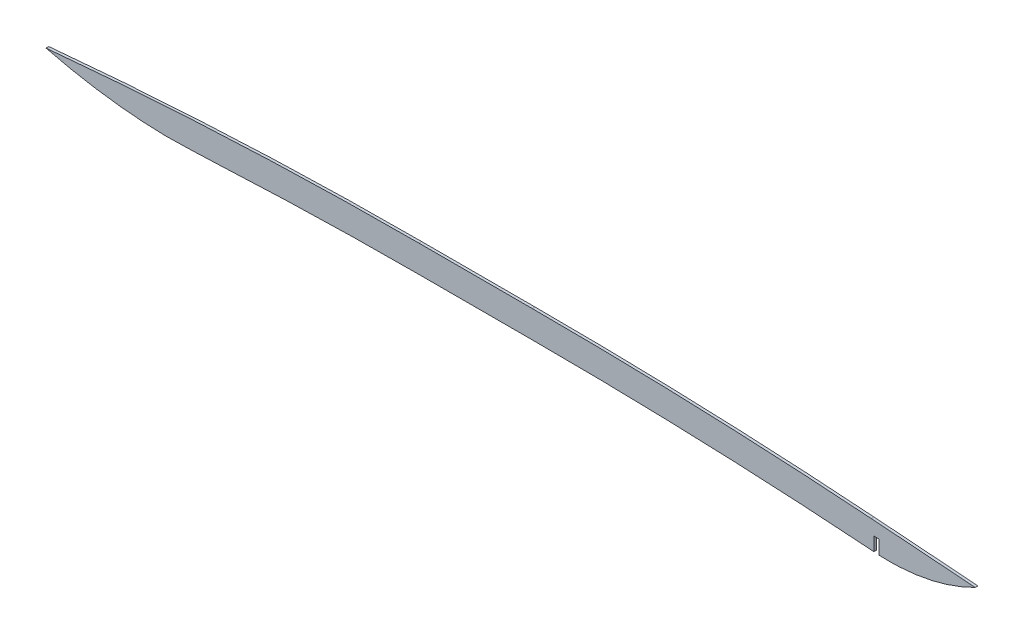
SolidWorks part; units mm, degrees
ref_plane "Front Plane" through (0, 0, 0) normal (0, 0, 1) x (1, 0, 0)
ref_plane "Top Plane" through (0, 0, 0) normal (0, 1, 0) x (1, 0, 0)
ref_plane "Right Plane" through (0, 0, 0) normal (1, 0, 0) x (0, 0, -1)
sketch "Sketch1" plane through (0, 0, 0) normal (0, 0, 1) x (1, 0, 0)
  line L2 (1659.5661, -5.4123) -> (2076.8952, -5.4123)
  line L3 (1659.5661, 94.5877) -> (2076.8952, 94.5877)
  arc A11 (3324.9617, 49.0573) -> (2946.0697, 72.5208) centre (2076.8952, -17033.9956) ccw
  arc A12 (2946.0697, 72.5208) -> (2677.8035, 84.0439) centre (2076.8952, -17033.9956) ccw
  arc A14 (1659.5661, -5.4123) -> (927.3706, -23.9029) centre (1659.5661, -14511.4611) ccw
  arc A15 (2674.2953, -15.8945) -> (2076.8952, -5.4123) centre (2076.8952, -17033.9956) ccw
  arc A16 (2940.9953, -27.3504) -> (2674.2953, -15.8945) centre (2076.8952, -17033.9956) ccw
  arc A17 (3317.6753, -50.6769) -> (2940.9953, -27.3504) centre (2076.8952, -17033.9956) ccw
  arc A18 (3701.2123, -79.0448) -> (3317.6753, -50.6769) centre (-16248.6371, -267195.9745) ccw
  arc A19 (4283.8008, -123.092) -> (3701.2123, -79.0448) centre (-16201.7377, -267199.4731) ccw
  arc A20 (2677.8035, 84.0439) -> (2076.8952, 94.5877) centre (2076.8952, -17033.9956) ccw
  arc A21 (1659.5661, 94.5877) -> (689.0096, 62.3058) centre (1659.5661, -14511.4611) ccw
  arc A22 (689.0096, 62.3058) -> (286.2522, 29.8824) centre (1659.5661, -14511.4611) ccw
  arc A23 (286.2522, 29.8824) -> (0, 0) centre (1659.5661, -14511.4611) ccw
  arc A24 (4636.8918, -50.106) -> (3708.6426, 20.6788) centre (-16201.7377, -267199.4731) ccw
  arc A25 (3708.6426, 20.6788) -> (3324.9617, 49.0573) centre (-16248.637, -267195.9745) ccw
  spline S0 degree 2 poles (0, 0) (462.6118, -45.5045) (927.3706, -23.9029) knots 0 0 0 1 1 1
  spline S1 degree 2 poles (4636.8918, -50.106) (4468.4256, -123.0197) (4283.8008, -123.092) knots 0 0 0 1 1 1
  spline S2 degree 2 poles (3708.6426, 20.6788) (3526.2676, -70.9076) (3317.6753, -50.6769) knots 0 0 0 1 1 1
  spline S3 degree 2 poles (286.2522, 29.8824) (603.9875, -50.658) (927.3706, -23.9029) knots 0 0 0 1 1 1
  point P1 (725.0006, -30.1296)
  point P12 (-15866.2384, -267056.2118)
  point P13 (4962.3108, -106.666)
  point P14 (3644.0374, -7.0823)
  point P21 (889.6553, -509.1767)
  point P22 (1995.0654, -14368.1998)
  point P23 (13.7533, -99.0497)
  point P33 (684.2924, 61.8793)
  point P35 (1648.2039, -14412.1087)
  point P36 (1648.2039, 93.9402)
  point P45 (3689.8501, 20.3076)
  point P47 (-16213.0999, -267100.1207)
  point P48 (4617.7529, -50.4507)
extrude "Boss-Extrude1" add sketch "Sketch1" along normal blind 10 contours S2 A25 A11 A12 A20 L3 A21 A22 A23 S0 A14 L2 A15 A16 A17 A18
sketch "Sketch2" plane through (0, 0, 10) normal (0, 0, 1) x (1, 0, 0)
  line L0 (3354.9574, -53.4101) -> (3354.9574, -1.9432)
  line L1 (3334.9574, -51.9432) -> (3334.9574, -1.9432)
  line L2 (3334.9574, -1.9432) -> (3354.9574, -1.9432)
  arc A4 (3354.9574, -53.4101) -> (3317.6753, -50.6769) centre (-16248.6371, -267195.9745) ccw construction
  arc A5 (3354.9574, -53.4101) -> (3334.9574, -51.9432) centre (-16248.6371, -267195.9745) ccw
  dimension "D1" = 20
  dimension "D2" = 50
extrude "Cut-Extrude1" cut sketch "Sketch2" against normal through all
